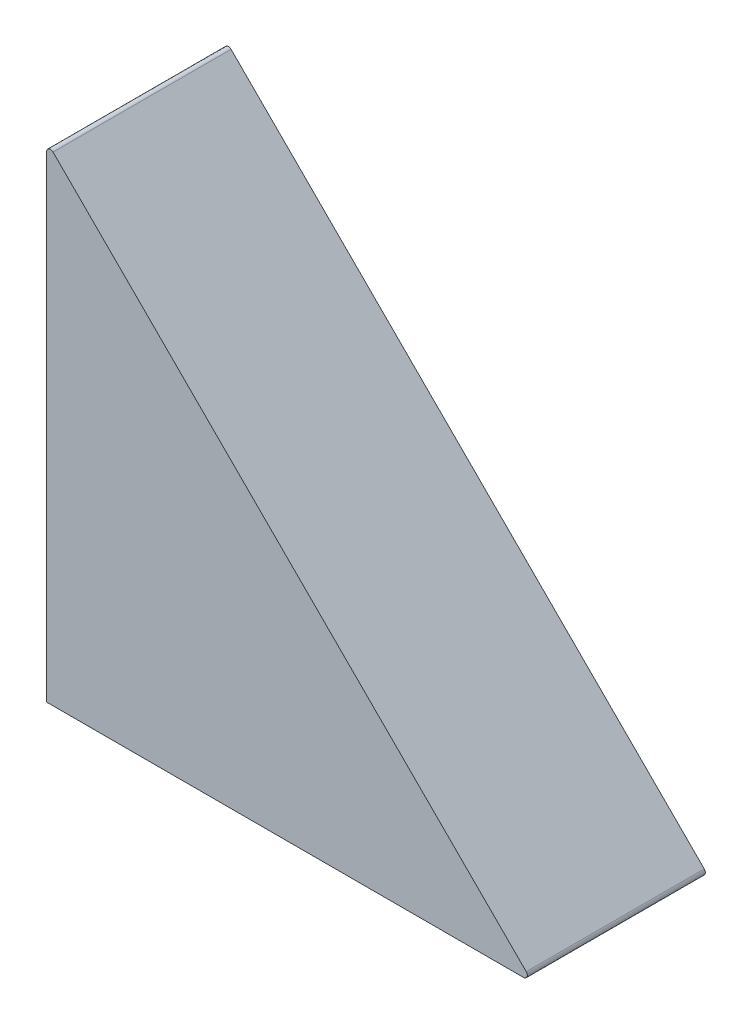
SolidWorks part; units mm, degrees
ref_plane "Front Plane" through (0, 0, 0) normal (0, 0, 1) x (1, 0, 0)
ref_plane "Top Plane" through (0, 0, 0) normal (0, 1, 0) x (1, 0, 0)
ref_plane "Right Plane" through (0, 0, 0) normal (1, 0, 0) x (0, 0, -1)
sketch "Sketch1" plane through (0, 0, 0) normal (0, 0, 1) x (1, 0, 0)
  line L0 (0, 0) -> (12.7586, 0)
  line L1 (12.8293, 0.1707) -> (0.1707, 12.8293)
  line L2 (0, 12.7586) -> (0, 0)
  arc A0 (12.7586, 0) -> (12.8293, 0.1707) centre (12.7586, 0.1) ccw
  arc A1 (0.1707, 12.8293) -> (0, 12.7586) centre (0.1, 12.7586) ccw
  point P6 (13, 0)
  point P9 (0, 13)
  dimension "D3" = 0.1
  dimension "D1" = 13
  dimension "D2" = 13
extrude "Boss-Extrude1" add sketch "Sketch1" along normal blind 4.7625
